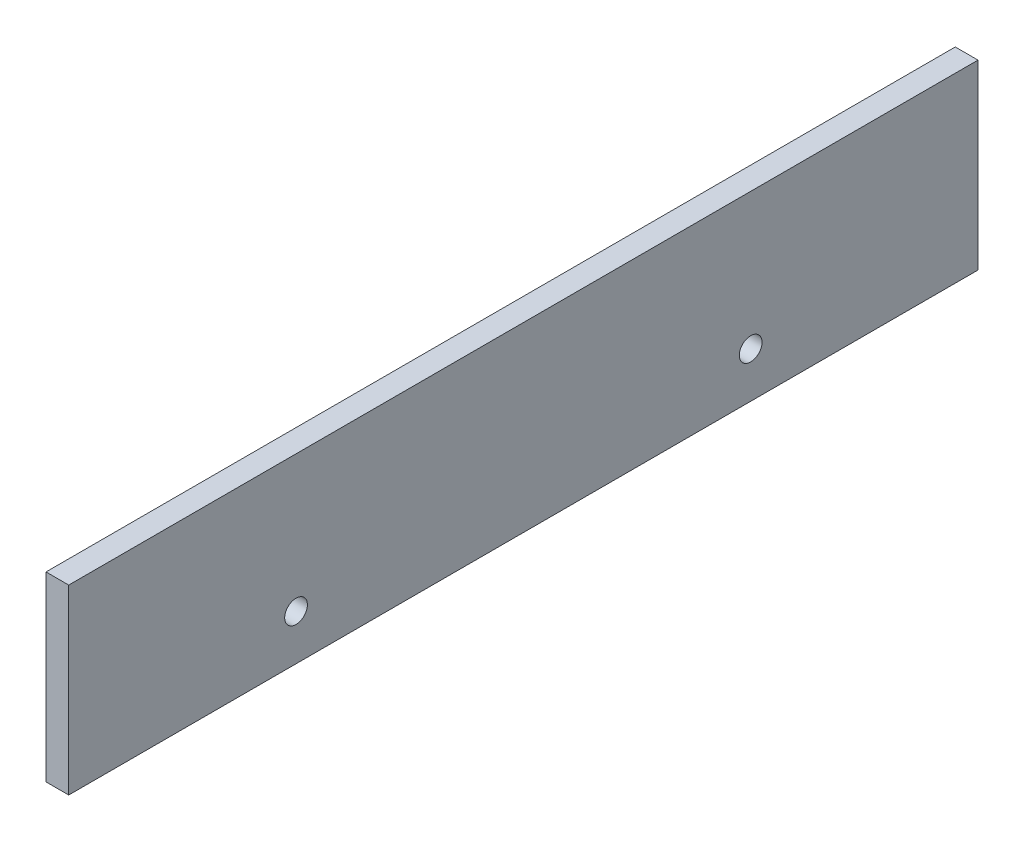
SolidWorks part; units mm, degrees
material "1060 合金"
ref_plane "前视基准面" through (0, 0, 0) normal (0, 0, 1) x (1, 0, 0)
ref_plane "上视基准面" through (0, 0, 0) normal (0, 1, 0) x (1, 0, 0)
ref_plane "右视基准面" through (0, 0, 0) normal (1, 0, 0) x (0, 0, -1)
other "Configuration Table"
sketch "草图1" plane through (0, 0, 0) normal (0, 0, 1) x (1, 0, 0)
  line L1 (-2.5, 20) -> (2.5, 20)
  line L2 (-2.5, 20) -> (-2.5, -20)
  line L3 (-2.5, -20) -> (2.5, -20)
  line L4 (2.5, 20) -> (2.5, -20)
  line L5 (-2.5, 20) -> (2.5, -20) construction
  line L6 (-2.5, -20) -> (2.5, 20) construction
  point P0 (0, 0)
  dimension "D1" = 5
  dimension "D2" = 40
extrude "凸台-拉伸1" add sketch "草图1" along normal blind 200
sketch "草图2" plane through (2.5, 0, 0) normal (1, 0, 0) x (0, 0, -1)
  line L0 (-200, -10) -> (0, -10) construction
  line L1 (-100, 20) -> (-100, -20) construction
  line L4 (0, -20) -> (0, 20)
  line L5 (0, 20) -> (-200, 20)
  line L6 (-200, 20) -> (-200, -20)
  line L7 (-200, -20) -> (0, -20)
  line L8 (0, -20) -> (0, 20)
  line L9 (0, 20) -> (-200, 20)
  line L10 (-200, 20) -> (-200, -20)
  line L11 (-200, -20) -> (0, -20)
  circle A0 centre (-150, -10) radius 2.5
  circle A1 centre (-50, -10) radius 2.5
  dimension "D3" = 5
  dimension "D4" = 100
  dimension "D2" = 20
  dimension "D1" = 0
extrude "切除-拉伸1" cut sketch "草图2" against normal through all contours A0 | A1
